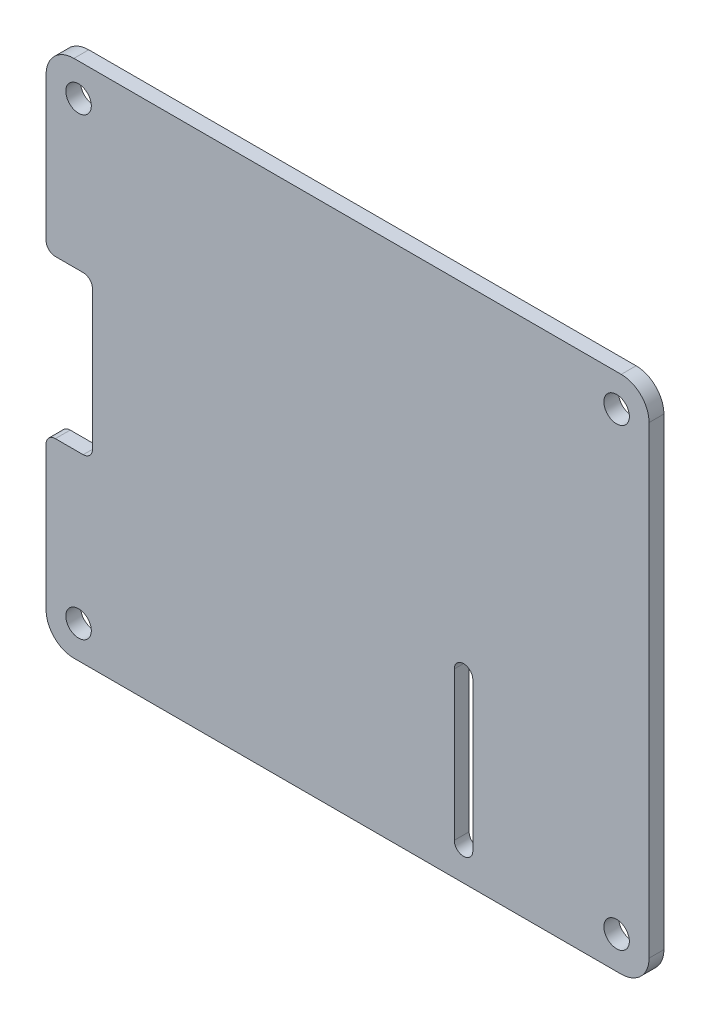
SolidWorks part; units mm, degrees
ref_plane "Front Plane" through (0, 0, 0) normal (0, 0, 1) x (1, 0, 0)
ref_plane "Top Plane" through (0, 0, 0) normal (0, 1, 0) x (1, 0, 0)
ref_plane "Right Plane" through (0, 0, 0) normal (1, 0, 0) x (0, 0, -1)
sketch "Sketch1" plane through (0, 0, 0) normal (0, 0, 1) x (1, 0, 0)
  line L0 (-32.5, 0) -> (19.9856, 0) construction
  line L1 (-29.5, -28) -> (29.5, -28)
  line L2 (-32.5, -25) -> (-32.5, -9.5)
  line L3 (-29.5, 28) -> (29.5, 28)
  line L4 (32.5, -25) -> (32.5, 25)
  line L5 (-32.5, -28) -> (32.5, 28) construction
  line L6 (-32.5, 28) -> (32.5, -28) construction
  line L7 (-27.5, -25) -> (-27.5, -23.6923)
  line L8 (-31.5, -8.5) -> (-28.5, -8.5)
  line L9 (-31.5, 8.5) -> (-28.5, 8.5)
  line L10 (-32.5, 9.5) -> (-32.5, 25)
  line L11 (-32.5, -25) -> (-32.5, 25) construction
  line L13 (-27.5, -25) -> (-27.5, 25) construction
  line L15 (-32.5, 8.5) -> (19.9856, 8.5) construction
  line L17 (-32.5, -8.5) -> (19.9856, -8.5) construction
  line L18 (-27.5, -7.5) -> (-27.5, 7.5)
  arc A0 (-32.5, -25) -> (-29.5, -28) centre (-29.5, -25) ccw
  arc A1 (29.5, -28) -> (32.5, -25) centre (29.5, -25) ccw
  arc A2 (32.5, 25) -> (29.5, 28) centre (29.5, 25) ccw
  arc A3 (-29.5, 28) -> (-32.5, 25) centre (-29.5, 25) ccw
  arc A4 (-32.5, -9.5) -> (-31.5, -8.5) centre (-31.5, -9.5) cw
  arc A5 (-27.5, -7.5) -> (-28.5, -8.5) centre (-28.5, -7.5) cw
  arc A6 (-32.5, 9.5) -> (-31.5, 8.5) centre (-31.5, 9.5) ccw
  arc A7 (-27.5, 7.5) -> (-28.5, 8.5) centre (-28.5, 7.5) ccw
  point P0 (0, 0)
  point P37 (-27.5, -8.5)
  point P48 (0, 0)
  dimension "D3" = 3
  dimension "D7" = 1
  dimension "D1" = 65
  dimension "D2" = 56
  dimension "D4" = 5
  dimension "D5" = 8.5
  dimension "D6" = 8.5
extrude "Boss-Extrude1" add sketch "Sketch1" along normal blind 1.6 contours L3 A2 L4 A1 L1 A0 L2 A4 L8 A5 L18 A7 L9 A6 L10 A3
sketch "Sketch3" plane through (0, 0, 1.6) normal (0, 0, 1) x (1, 0, 0)
  line L0 (12.5, -8.5) -> (12.5, -24.5) construction
  line L1 (13.5, -8.5) -> (13.5, -24.5)
  line L2 (11.5, -8.5) -> (11.5, -24.5)
  line L3 (-29.5, -28) -> (29.5, -28) construction
  line L4 (-32.5, -25) -> (-32.5, -9.5) construction
  arc A0 (13.5, -8.5) -> (11.5, -8.5) centre (12.5, -8.5) ccw
  arc A1 (11.5, -24.5) -> (13.5, -24.5) centre (12.5, -24.5) ccw
  point P2 (12.5, -16.5)
  point P7 (12.5, -25.5)
  dimension "D2" = 17
  dimension "D1" = 2
  dimension "D3" = 11.5
  dimension "D4" = 45
extrude "Cut-Extrude1" cut sketch "Sketch3" against normal through all
sketch "Sketch4" plane through (0, 0, 1.6) normal (0, 0, 1) x (1, 0, 0)
  line L0 (-29.5, 28) -> (29.5, 28) construction
  line L1 (-32.5, 9.5) -> (-32.5, 25) construction
  line L2 (32.5, 0) -> (-33.9713, 0) construction
  line L3 (32.5, -25) -> (32.5, 25) construction
  circle A0 centre (-29, 24.5) radius 1.375
  circle A1 centre (29, 24.5) radius 1.375
  circle A2 centre (29, -24.5) radius 1.375
  circle A3 centre (-29, -24.5) radius 1.375
  dimension "D1" = 3.5
  dimension "D2" = 2.75
  dimension "D3" = 3.5
  dimension "D4" = 2
extrude "Cut-Extrude2" cut sketch "Sketch4" against normal through all
